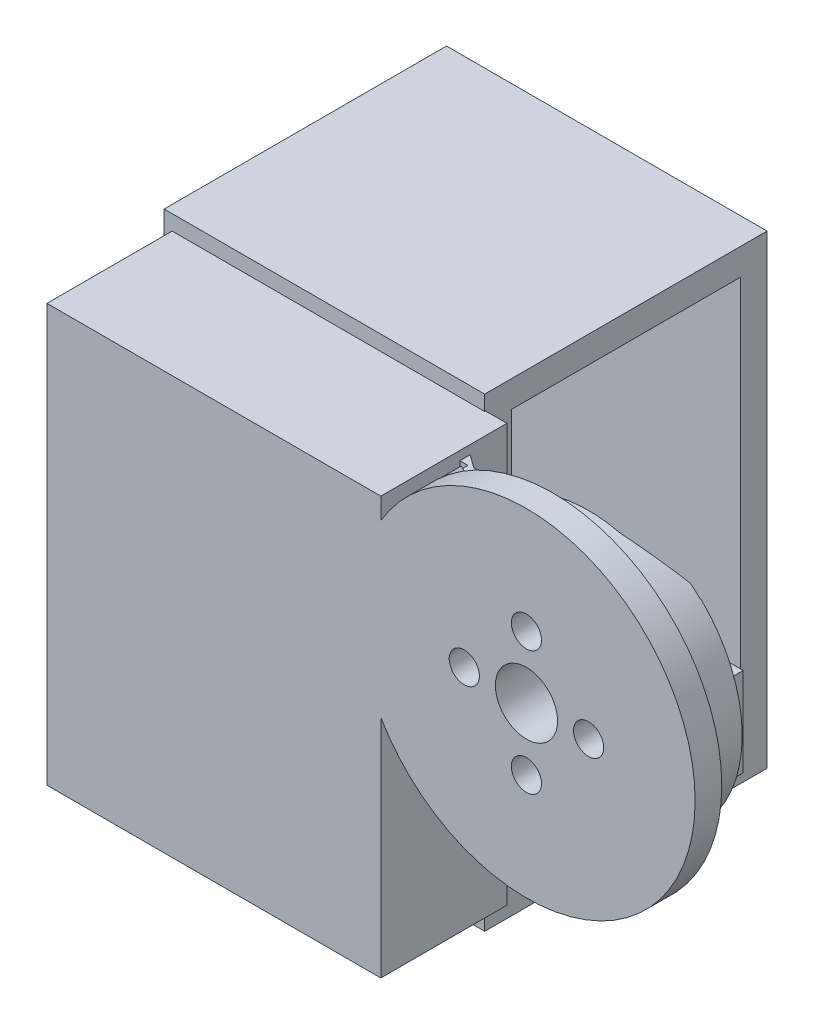
SolidWorks part; units mm, degrees
ref_plane "Front Plane" through (0, 0, 0) normal (0, 0, 1) x (1, 0, 0)
ref_plane "Top Plane" through (0, 0, 0) normal (0, 1, 0) x (1, 0, 0)
ref_plane "Right Plane" through (0, 0, 0) normal (1, 0, 0) x (0, 0, -1)
ref_plane "PZ_p23_000" through (0, 0, 23) normal (0, 0, 1) x (1, 0, 0)
sketch "S_cyl1" plane through (0, 0, 23) normal (0, 0, 1) x (1, 0, 0)
  circle A0 centre (0, 0) radius 19
  dimension "D1_S_cyl1" = 38
extrude "Boss_1" add sketch "S_cyl1" along normal blind 7
ref_plane "PZ_p21_000" through (0, 0, 21) normal (0, 0, 1) x (1, 0, 0)
sketch "S_prism2" plane through (0, 0, 21) normal (0, 0, 1) x (1, 0, 0)
  line L0 (-15.4919, -11) -> (15.4919, -11)
  line L1 (15.4919, 11) -> (-15.4919, 11)
  arc A0 (15.4919, -11) -> (15.4919, 11) centre (0, 0) ccw
  arc A1 (-15.4919, 11) -> (-15.4919, -11) centre (0, 0) ccw
extrude "Boss_2" add sketch "S_prism2" along normal blind 2.1
ref_plane "PZ_p19_600" through (0, 0, 19.6) normal (0, 0, 1) x (1, 0, 0)
sketch "S_box3" plane through (0, 0, 19.6) normal (0, 0, 1) x (1, 0, 0)
  line L0 (-14.2, -5) -> (14, -5)
  line L1 (14, -5) -> (14, 5)
  line L2 (14, 5) -> (-14.2, 5)
  line L3 (-14.2, 5) -> (-14.2, -5)
  dimension "P1" = 14.2
  dimension "P2" = 5
  dimension "P3" = 14
  dimension "P4" = 5
  dimension "P5" = 14
  dimension "P6" = 5
  dimension "P7" = 14.2
  dimension "P8" = 5
extrude "Boss_3" add sketch "S_box3" along normal blind 1.5
ref_plane "PZ_p15_800" through (0, 0, 15.8) normal (0, 0, 1) x (1, 0, 0)
sketch "S_box4" plane through (0, 0, 15.8) normal (0, 0, 1) x (1, 0, 0)
  line L0 (-54, -35) -> (-16.4, -35)
  line L1 (-16.4, -35) -> (-16.4, 12)
  line L2 (-16.4, 12) -> (-54, 12)
  line L3 (-54, 12) -> (-54, -35)
  dimension "P1" = 54
  dimension "P2" = 35
  dimension "P3" = 16.4
  dimension "P4" = 35
  dimension "P5" = 16.4
  dimension "P6" = 12
  dimension "P7" = 54
  dimension "P8" = 12
extrude "Boss_4" add sketch "S_box4" along normal blind 14.2
ref_plane "PX_m11_500" through (-11.5, 0, 0) normal (1, 0, 0) x (0, 0, -1)
sketch "S_prism5" plane through (-11.5, 0, 0) normal (1, 0, 0) x (0, 0, -1)
  line L0 (-21.05, -11) -> (-21.05, 12)
  line L1 (-21.05, 12) -> (-23.1, 15)
  line L2 (-23.1, 15) -> (-23.1, -12.5)
  line L3 (-23.1, -12.5) -> (-21.05, -11)
extrude "Boss_5" add sketch "S_prism5" along normal blind 23
ref_plane "PY_m11_000" through (0, -11, 0) normal (0, 1, 0) x (1, 0, 0)
sketch "S_prism6" plane through (0, -11, 0) normal (0, 1, 0) x (1, 0, 0)
  line L0 (-16.45, -21.1) -> (-16.45, -19.9)
  line L1 (-16.45, -19.9) -> (-14.8, -21.1)
  line L2 (-14.8, -21.1) -> (-16.45, -21.1)
extrude "Boss_6" add sketch "S_prism6" along normal blind 22
ref_plane "PZ_m15_900" through (0, 0, -15.9) normal (0, 0, 1) x (1, 0, 0)
sketch "S_box7" plane through (0, 0, -15.9) normal (0, 0, 1) x (1, 0, 0)
  line L0 (-54.9, -38.7) -> (-18.8, -38.7)
  line L1 (-18.8, -38.7) -> (-18.8, -35.7)
  line L2 (-18.8, -35.7) -> (-54.9, -35.7)
  line L3 (-54.9, -35.7) -> (-54.9, -38.7)
  dimension "P1" = 54.9
  dimension "P2" = 38.7
  dimension "P3" = 18.8
  dimension "P4" = 38.7
  dimension "P5" = 18.8
  dimension "P6" = 35.7
  dimension "P7" = 54.9
  dimension "P8" = 35.7
extrude "Boss_7" add sketch "S_box7" along normal blind 31.8
sketch "S_box8" plane through (0, 0, -15.9) normal (0, 0, 1) x (1, 0, 0)
  line L0 (-54.9, 10.7) -> (-18.8, 10.7)
  line L1 (-18.8, 10.7) -> (-18.8, 13.7)
  line L2 (-18.8, 13.7) -> (-54.9, 13.7)
  line L3 (-54.9, 13.7) -> (-54.9, 10.7)
  dimension "P1" = 54.9
  dimension "P2" = 10.7
  dimension "P3" = 18.8
  dimension "P4" = 10.7
  dimension "P5" = 18.8
  dimension "P6" = 13.7
  dimension "P7" = 54.9
  dimension "P8" = 13.7
extrude "Boss_8" add sketch "S_box8" along normal blind 31.8
sketch "S_box9" plane through (0, 0, -15.9) normal (0, 0, 1) x (1, 0, 0)
  line L0 (-54.9, -38.7) -> (-18.8, -38.7)
  line L1 (-18.8, -38.7) -> (-18.8, 13.7)
  line L2 (-18.8, 13.7) -> (-54.9, 13.7)
  line L3 (-54.9, 13.7) -> (-54.9, -38.7)
  dimension "P1" = 54.9
  dimension "P2" = 38.7
  dimension "P3" = 18.8
  dimension "P4" = 38.7
  dimension "P5" = 18.8
  dimension "P6" = 13.7
  dimension "P7" = 54.9
  dimension "P8" = 13.7
extrude "Boss_9" add sketch "S_box9" along normal blind 3
ref_plane "PZ_p12_900" through (0, 0, 12.9) normal (0, 0, 1) x (1, 0, 0)
sketch "S_box10" plane through (0, 0, 12.9) normal (0, 0, 1) x (1, 0, 0)
  line L0 (-54.9, -38.7) -> (-18.8, -38.7)
  line L1 (-18.8, -38.7) -> (-18.8, 13.7)
  line L2 (-18.8, 13.7) -> (-54.9, 13.7)
  line L3 (-54.9, 13.7) -> (-54.9, -38.7)
  dimension "P1" = 54.9
  dimension "P2" = 38.7
  dimension "P3" = 18.8
  dimension "P4" = 38.7
  dimension "P5" = 18.8
  dimension "P6" = 13.7
  dimension "P7" = 54.9
  dimension "P8" = 13.7
extrude "Boss_10" add sketch "S_box10" along normal blind 3
sketch "S_box11" plane through (0, 0, -15.9) normal (0, 0, 1) x (1, 0, 0)
  line L0 (-54.9, -38.7) -> (-50.3, -38.7)
  line L1 (-50.3, -38.7) -> (-50.3, 13.7)
  line L2 (-50.3, 13.7) -> (-54.9, 13.7)
  line L3 (-54.9, 13.7) -> (-54.9, -38.7)
  dimension "P1" = 54.9
  dimension "P2" = 38.7
  dimension "P3" = 50.3
  dimension "P4" = 38.7
  dimension "P5" = 50.3
  dimension "P6" = 13.7
  dimension "P7" = 54.9
  dimension "P8" = 13.7
extrude "Boss_11" add sketch "S_box11" along normal blind 31.8
ref_plane "PX_m55_000" through (-55, 0, 0) normal (1, 0, 0) x (0, 0, -1)
sketch "S_hole12" plane through (-55, 0, 0) normal (1, 0, 0) x (0, 0, -1)
  circle A0 centre (0, 0) radius 10.5
  dimension "D1_S_hole12" = 21
extrude "Hole_12" cut sketch "S_hole12" along normal blind 4.8
ref_plane "PZ_m9_700" through (0, 0, -9.7) normal (0, 0, 1) x (1, 0, 0)
sketch "S_cut13" plane through (0, 0, -9.7) normal (0, 0, 1) x (1, 0, 0)
  line L0 (-55, -30.4) -> (-50.25, -30.4)
  line L1 (-50.25, -30.4) -> (-50.25, -10.9)
  line L2 (-50.25, -10.9) -> (-55, -10.9)
  line L3 (-55, -10.9) -> (-55, -30.4)
  dimension "P1" = 55
  dimension "P2" = 30.4
  dimension "P3" = 50.25
  dimension "P4" = 30.4
  dimension "P5" = 50.25
  dimension "P6" = 10.9
  dimension "P7" = 55
  dimension "P8" = 10.9
extrude "Pocket_13" cut sketch "S_cut13" along normal blind 19.4
ref_plane "PZ_m8_200" through (0, 0, -8.2) normal (0, 0, 1) x (1, 0, 0)
sketch "S_cut14" plane through (0, 0, -8.2) normal (0, 0, 1) x (1, 0, 0)
  line L0 (-55, -39.2) -> (-50.25, -39.2)
  line L1 (-50.25, -39.2) -> (-50.25, -30.4)
  line L2 (-50.25, -30.4) -> (-55, -30.4)
  line L3 (-55, -30.4) -> (-55, -39.2)
  dimension "P1" = 55
  dimension "P2" = 39.2
  dimension "P3" = 50.25
  dimension "P4" = 39.2
  dimension "P5" = 50.25
  dimension "P6" = 30.4
  dimension "P7" = 55
  dimension "P8" = 30.4
extrude "Pocket_14" cut sketch "S_cut14" along normal blind 16.4
ref_plane "PZ_m3_500" through (0, 0, -3.5) normal (0, 0, 1) x (1, 0, 0)
sketch "S_cut15" plane through (0, 0, -3.5) normal (0, 0, 1) x (1, 0, 0)
  line L0 (-55, -11) -> (-50.25, -11)
  line L1 (-50.25, -11) -> (-50.25, 0)
  line L2 (-50.25, 0) -> (-55, 0)
  line L3 (-55, 0) -> (-55, -11)
  dimension "P1" = 55
  dimension "P2" = 11
  dimension "P3" = 50.25
  dimension "P4" = 11
  dimension "P5" = 50.25
  dimension "P6" = 55
extrude "Pocket_15" cut sketch "S_cut15" along normal blind 7
ref_plane "PZ_m16_400" through (0, 0, -16.4) normal (0, 0, 1) x (1, 0, 0)
sketch "S_cut16" plane through (0, 0, -16.4) normal (0, 0, 1) x (1, 0, 0)
  line L0 (-55.1, -10) -> (-52.2, -10)
  line L1 (-52.2, -10) -> (-52.2, 10)
  line L2 (-52.2, 10) -> (-55.1, 10)
  line L3 (-55.1, 10) -> (-55.1, -10)
  dimension "P1" = 55.1
  dimension "P2" = 10
  dimension "P3" = 52.2
  dimension "P4" = 10
  dimension "P5" = 52.2
  dimension "P6" = 10
  dimension "P7" = 55.1
  dimension "P8" = 10
extrude "Pocket_16" cut sketch "S_cut16" along normal blind 16.4
sketch "S_hole17" plane through (-55, 0, 0) normal (1, 0, 0) x (0, 0, -1)
  circle A0 centre (-10.25, -8.3) radius 1.1
  dimension "D1_S_hole17" = 2.2
  dimension "P2" = 10.25
  dimension "P3" = 8.3
extrude "Hole_17" cut sketch "S_hole17" along normal blind 4.8
sketch "S_hole18" plane through (-55, 0, 0) normal (1, 0, 0) x (0, 0, -1)
  circle A0 centre (-10.25, -8.3) radius 2.3
  dimension "D1_S_hole18" = 4.6
  dimension "P2" = 10.25
  dimension "P3" = 8.3
extrude "Hole_18" cut sketch "S_hole18" along normal blind 1.7
sketch "S_hole19" plane through (-55, 0, 0) normal (1, 0, 0) x (0, 0, -1)
  circle A0 centre (10.25, -32.75) radius 1.1
  dimension "D1_S_hole19" = 2.2
  dimension "P2" = 10.25
  dimension "P3" = 32.75
extrude "Hole_19" cut sketch "S_hole19" along normal blind 4.8
sketch "S_hole20" plane through (-55, 0, 0) normal (1, 0, 0) x (0, 0, -1)
  circle A0 centre (10.25, -32.75) radius 2.3
  dimension "D1_S_hole20" = 4.6
  dimension "P2" = 10.25
  dimension "P3" = 32.75
extrude "Hole_20" cut sketch "S_hole20" along normal blind 1.7
sketch "S_hole21" plane through (-55, 0, 0) normal (1, 0, 0) x (0, 0, -1)
  circle A0 centre (-10.25, -32.75) radius 1.1
  dimension "D1_S_hole21" = 2.2
  dimension "P2" = 10.25
  dimension "P3" = 32.75
extrude "Hole_21" cut sketch "S_hole21" along normal blind 4.8
sketch "S_hole22" plane through (-55, 0, 0) normal (1, 0, 0) x (0, 0, -1)
  circle A0 centre (-10.25, -32.75) radius 2.3
  dimension "D1_S_hole22" = 4.6
  dimension "P2" = 10.25
  dimension "P3" = 32.75
extrude "Hole_22" cut sketch "S_hole22" along normal blind 1.7
ref_plane "PZ_p20_900" through (0, 0, 20.9) normal (0, 0, 1) x (1, 0, 0)
sketch "S_pcut23" plane through (0, 0, 20.9) normal (0, 0, 1) x (1, 0, 0)
  line L0 (-14.7923, 12.8588) -> (-11.5471, 10.0377)
  line L1 (7.8801, -13.1147) -> (10.0947, -16.8005)
  arc A0 (10.0947, -16.8005) -> (-14.7923, 12.8588) centre (0, 0) ccw
  arc A1 (-11.5471, 10.0377) -> (7.8801, -13.1147) centre (0, 0) cw
extrude "Cut_23" cut sketch "S_pcut23" along normal blind 6.1
ref_plane "PZ_p19_500" through (0, 0, 19.5) normal (0, 0, 1) x (1, 0, 0)
sketch "S_hole24" plane through (0, 0, 19.5) normal (0, 0, 1) x (1, 0, 0)
  circle A0 centre (0, 0) radius 3.5
  dimension "D1_S_hole24" = 7
extrude "Hole_24" cut sketch "S_hole24" along normal blind 10.6
sketch "S_hole25" plane through (0, 0, 19.5) normal (0, 0, 1) x (1, 0, 0)
  circle A0 centre (7, 0) radius 1.7
  dimension "D1_S_hole25" = 3.4
  dimension "P2" = 7
extrude "Hole_25" cut sketch "S_hole25" along normal blind 10.6
sketch "S_hole26" plane through (0, 0, 19.5) normal (0, 0, 1) x (1, 0, 0)
  circle A0 centre (0, 7) radius 1.7
  dimension "D1_S_hole26" = 3.4
  dimension "P2" = 7
extrude "Hole_26" cut sketch "S_hole26" along normal blind 10.6
sketch "S_hole27" plane through (0, 0, 19.5) normal (0, 0, 1) x (1, 0, 0)
  circle A0 centre (-7, 0) radius 1.7
  dimension "D1_S_hole27" = 3.4
  dimension "P2" = 7
extrude "Hole_27" cut sketch "S_hole27" along normal blind 10.6
sketch "S_hole28" plane through (0, 0, 19.5) normal (0, 0, 1) x (1, 0, 0)
  circle A0 centre (0, -7) radius 1.7
  dimension "D1_S_hole28" = 3.4
  dimension "P2" = 7
extrude "Hole_28" cut sketch "S_hole28" along normal blind 10.6
ref_plane "PZ_p19_400" through (0, 0, 19.4) normal (0, 0, 1) x (1, 0, 0)
sketch "S_hole29" plane through (0, 0, 19.4) normal (0, 0, 1) x (1, 0, 0)
  circle A0 centre (7, 0) radius 3.2
  dimension "D1_S_hole29" = 6.4
  dimension "P2" = 7
extrude "Hole_29" cut sketch "S_hole29" along normal blind 7.6
sketch "S_hole30" plane through (0, 0, 19.4) normal (0, 0, 1) x (1, 0, 0)
  circle A0 centre (0, 7) radius 3.2
  dimension "D1_S_hole30" = 6.4
  dimension "P2" = 7
extrude "Hole_30" cut sketch "S_hole30" along normal blind 7.6
sketch "S_hole31" plane through (0, 0, 19.4) normal (0, 0, 1) x (1, 0, 0)
  circle A0 centre (-7, 0) radius 3.2
  dimension "D1_S_hole31" = 6.4
  dimension "P2" = 7
extrude "Hole_31" cut sketch "S_hole31" along normal blind 7.6
sketch "S_hole32" plane through (0, 0, 19.4) normal (0, 0, 1) x (1, 0, 0)
  circle A0 centre (0, -7) radius 3.2
  dimension "D1_S_hole32" = 6.4
  dimension "P2" = 7
extrude "Hole_32" cut sketch "S_hole32" along normal blind 7.6
equation "\"plate_t\" = 3"
equation "\"clearance\" = 0.5"
